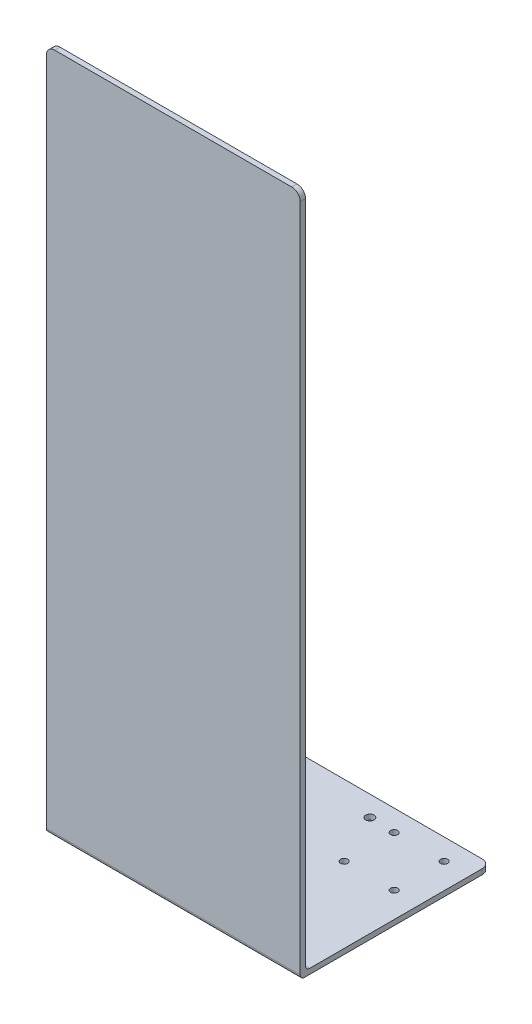
SolidWorks part; units mm, degrees
ref_plane "Front Plane" through (0, 0, 0) normal (0, 0, 1) x (1, 0, 0)
ref_plane "Top Plane" through (0, 0, 0) normal (0, 1, 0) x (1, 0, 0)
ref_plane "Right Plane" through (0, 0, 0) normal (1, 0, 0) x (0, 0, -1)
sketch "Sketch1" plane through (0, 0, 0) normal (0, 1, 0) x (1, 0, 0)
  line L1 (76.2, -57.15) -> (-76.2, -57.15)
  line L2 (76.2, -57.15) -> (76.2, 57.15)
  line L3 (76.2, 57.15) -> (-76.2, 57.15)
  line L4 (-76.2, -57.15) -> (-76.2, 57.15)
  line L5 (76.2, -57.15) -> (-76.2, 57.15) construction
  line L6 (76.2, 57.15) -> (-76.2, -57.15) construction
  point P0 (0, 0)
  dimension "D1" = 152.4
  dimension "D2" = 114.3
extrude "Boss-Extrude1" add sketch "Sketch1" along normal blind 3.175
sketch "Sketch2" plane through (0, 3.175, 0) normal (0, 1, 0) x (1, 0, 0)
  line L5 (76.2, -57.15) -> (76.2, 57.15) construction
  line L6 (-76.2, -57.15) -> (76.2, -57.15)
  line L7 (-76.2, -57.15) -> (-76.2, -53.975)
  line L8 (-76.2, -53.975) -> (76.2, -53.975)
  line L9 (76.2, -57.15) -> (76.2, -53.975)
  dimension "D1" = 3.175
extrude "Boss-Extrude2" add sketch "Sketch2" along normal blind 406.4
fillet "Fillet1" radius 2.54 2 edges at (0, 3.175, 53.975) (0, 0, 57.15)
fillet "Fillet2" radius 5.08 4 edges at (-76.2, 409.575, 55.5625) (76.2, 409.575, 55.5625) (-76.2, 1.5875, -57.15) (76.2, 1.5875, -57.15)
sketch "Sketch3" plane through (0, 3.175, 0) normal (0, 1, 0) x (1, 0, 0)
  line L0 (71.12, 57.15) -> (-71.12, 57.15) construction
  line L1 (-76.2, 52.07) -> (-76.2, -54.61) construction
  line L2 (-76.2, 52.07) -> (-76.2, -51.435) construction
  circle A0 centre (-25.4, 3.81) radius 30.988
  circle A1 centre (-66.675, 45.085) radius 2.54
  circle A2 centre (-66.675, -37.465) radius 2.54
  circle A3 centre (15.875, -37.465) radius 2.54
  circle A4 centre (15.875, 44.958) radius 2.54
  circle A5 centre (30.9386, 14.478) radius 2.159
  circle A6 centre (60.96, 14.478) radius 2.159
  circle A7 centre (30.988, 44.45) radius 2.159
  circle A8 centre (60.9386, 44.46) radius 2.15
  dimension "D3" = 61.976
  dimension "D4" = 4.3
  dimension "D5" = 4.318
  dimension "D6" = 4.318
  dimension "D7" = 4.318
  dimension "D8" = 5.08
  dimension "D9" = 5.08
  dimension "D10" = 5.08
  dimension "D11" = 5.08
  dimension "D1" = 53.34
  dimension "D2" = 50.8
  dimension "D12" = 12.065
  dimension "D13" = 9.525
  dimension "D14" = 94.615
  dimension "D15" = 9.525
  dimension "D16" = 92.075
  dimension "D17" = 12.192
  dimension "D18" = 94.615
  dimension "D19" = 92.075
  dimension "D20" = 107.188
  dimension "D21" = 137.1386
  dimension "D22" = 12.7
  dimension "D23" = 42.672
  dimension "D24" = 12.69
  dimension "D25" = 42.672
  dimension "D26" = 107.1386
  dimension "D27" = 137.16
extrude "Cut-Extrude1" cut sketch "Sketch3" against normal through all contours A0 | A4 | A2 | A3 | A7 | A8 | A6 | A5 | A1
